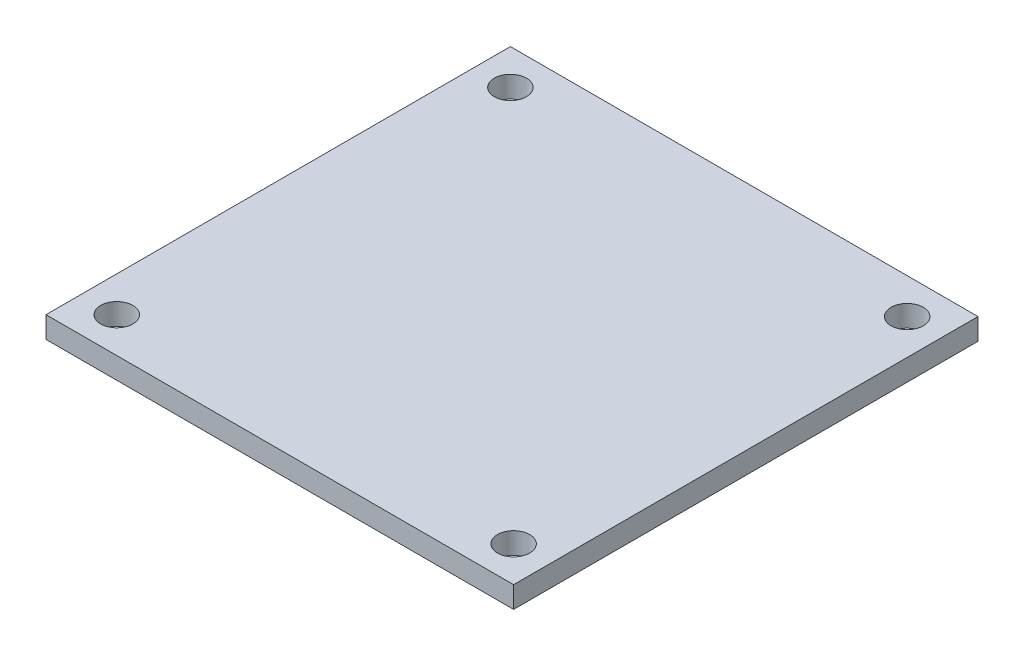
SolidWorks part; units mm, degrees
ref_plane "Plan de face" through (0, 0, 0) normal (0, 0, 1) x (1, 0, 0)
ref_plane "Plan de dessus" through (0, 0, 0) normal (0, 1, 0) x (1, 0, 0)
ref_plane "Plan de droite" through (0, 0, 0) normal (1, 0, 0) x (0, 0, -1)
sketch "Esquisse1" plane through (0, 0, 0) normal (0, 1, 0) x (1, 0, 0)
  line L0 (21.8, 43.3) -> (21.8, 0) construction
  line L1 (0, 0) -> (43.6, 0)
  line L2 (0, 0) -> (0, 43.3)
  line L3 (0, 43.3) -> (43.6, 43.3)
  line L4 (43.6, 0) -> (43.6, 43.3)
  line L5 (0, 21.65) -> (43.6, 21.65) construction
  circle A0 centre (3.3, 40) radius 1.5
  circle A1 centre (40.3, 40) radius 1.5
  circle A2 centre (40.3, 3.3) radius 1.5
  circle A3 centre (3.3, 3.3) radius 1.5
  dimension "D1" = 3
  dimension "D5" = 3.3
  dimension "D2" = 43.6
  dimension "D3" = 43.3
  dimension "D4" = 3.3
extrude "Boss.-Extru.1" add sketch "Esquisse1" along normal blind 2
